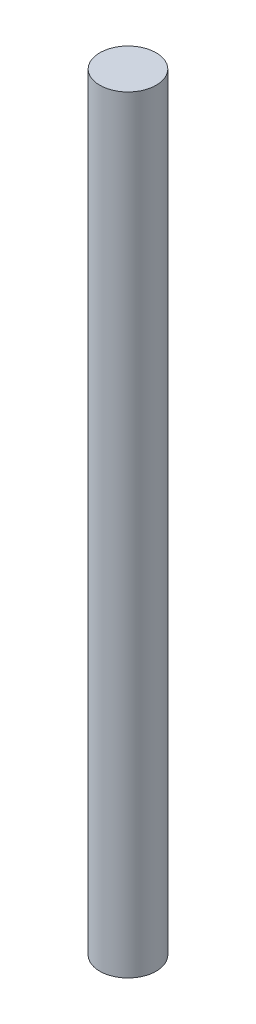
SolidWorks part; units mm, degrees
ref_plane "Front Plane" through (0, 0, 0) normal (0, 0, 1) x (1, 0, 0)
ref_plane "Top Plane" through (0, 0, 0) normal (0, 1, 0) x (1, 0, 0)
ref_plane "Right Plane" through (0, 0, 0) normal (1, 0, 0) x (0, 0, -1)
sketch "Sketch1" plane through (0, 0, 0) normal (0, 1, 0) x (1, 0, 0)
  circle A0 centre (0, 0) radius 80.75
  dimension "D1" = 161.5
extrude "Boss-Extrude1" add sketch "Sketch1" along normal blind 2200
